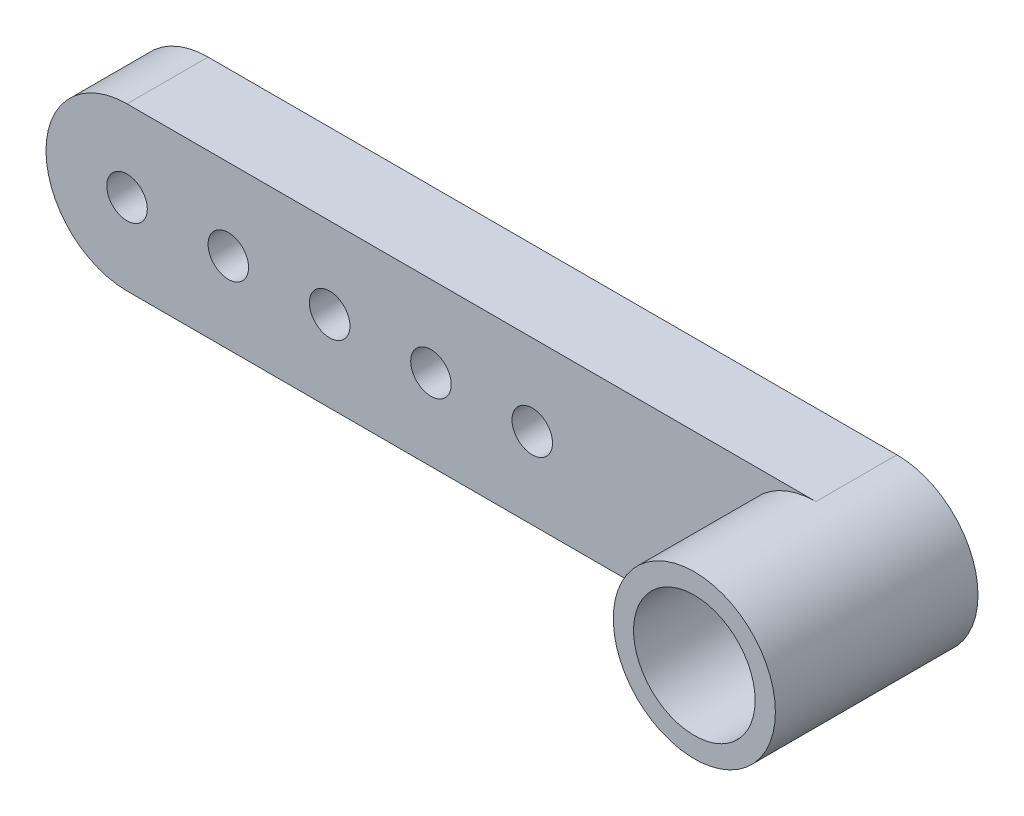
SolidWorks part; units mm, degrees
ref_plane "前视基准面" through (0, 0, 0) normal (0, 0, 1) x (1, 0, 0)
ref_plane "上视基准面" through (0, 0, 0) normal (0, 1, 0) x (1, 0, 0)
ref_plane "右视基准面" through (0, 0, 0) normal (1, 0, 0) x (0, 0, -1)
sketch "草图2" plane through (0, 0, 0) normal (0, 0, 1) x (1, 0, 0)
  line L0 (-8.5, 0) -> (8.5, 0) construction
  line L1 (-8.5, 2) -> (8.5, 2)
  line L2 (-8.5, -2) -> (8.5, -2)
  arc A0 (-8.5, 2) -> (-8.5, -2) centre (-8.5, 0) ccw
  arc A1 (8.5, -2) -> (8.5, 2) centre (8.5, 0) ccw
  point P2 (0, 0)
  dimension "D1" = 2
  dimension "D2" = 17
extrude "凸台-拉伸1" add sketch "草图2" along normal blind 2
sketch "草图3" plane through (0, 0, 2) normal (0, 0, 1) x (1, 0, 0)
  circle A0 centre (8.5, 0) radius 2
  arc A1 (8.5, -2) -> (8.5, 2) centre (8.5, 0) ccw construction
extrude "凸台-拉伸2" add sketch "草图3" along normal blind 3
sketch "草图4" plane through (0, 0, 5) normal (0, 0, 1) x (1, 0, 0)
  circle A0 centre (8.5, 0) radius 1.5
  dimension "D1" = 3
extrude "切除-拉伸1" cut sketch "草图4" against normal blind 4
sketch "草图5" plane through (0, 0, 1) normal (0, 0, 1) x (1, 0, 0)
  circle A0 centre (8.5, 0) radius 1
  dimension "D1" = 2
extrude "切除-拉伸2" cut sketch "草图5" against normal blind 4
sketch "草图6" plane through (0, 0, 0) normal (0, 0, -1) x (-1, 0, 0)
  line L0 (-1.5, 0) -> (0, 0) construction
  line L1 (8.5, 2) -> (8.5, -2) construction
  circle A0 centre (-1.5, 0) radius 0.5
  circle A1 centre (1, 0) radius 0.5
  circle A2 centre (3.5, 0) radius 0.5
  circle A3 centre (6, 0) radius 0.5
  circle A4 centre (8.5, 0) radius 0.5
  arc A6 (8.5, -2) -> (8.5, 2) centre (8.5, 0) ccw construction
  point P19 (8.5, 0)
  point P20 (-1.4443, 0)
  dimension "D1" = 1
  dimension "D3" = 2.5
  dimension "D2" = 5
extrude "切除-拉伸3" cut sketch "草图6" against normal blind 10
